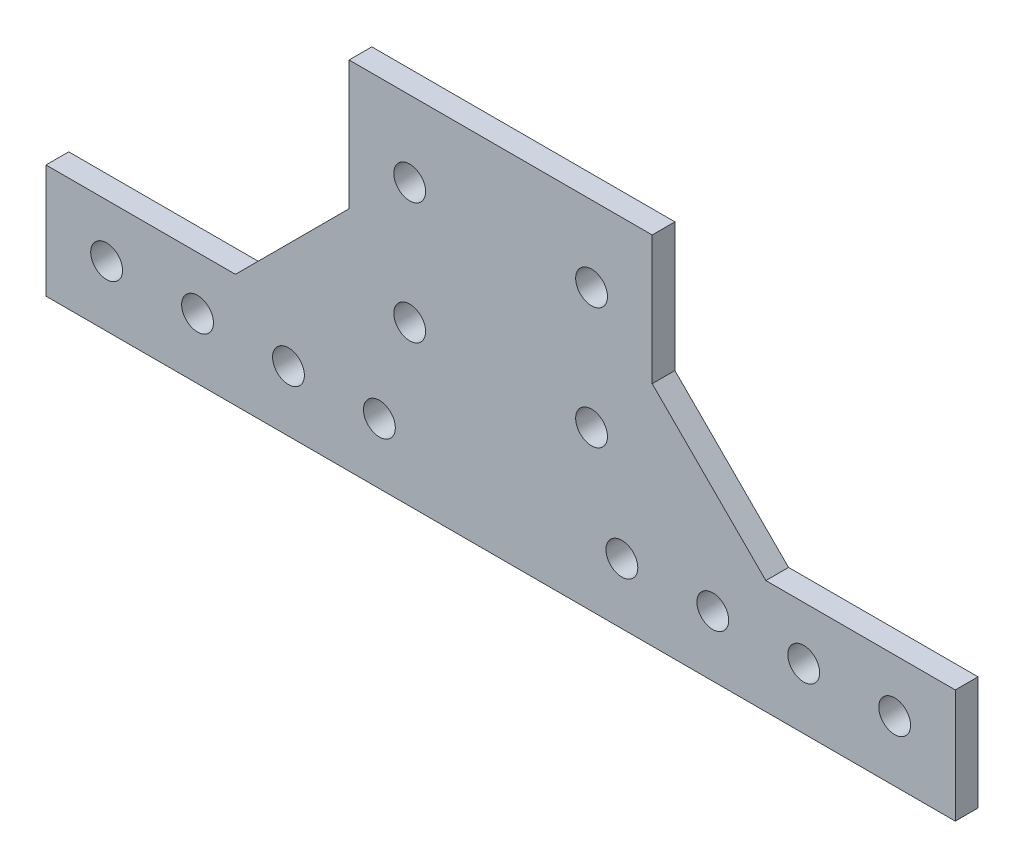
SolidWorks part; units mm, degrees
material "Thornel VCB-20 碳布"
ref_plane "前视基准面" through (0, 0, 0) normal (0, 0, 1) x (1, 0, 0)
ref_plane "上视基准面" through (0, 0, 0) normal (0, 1, 0) x (1, 0, 0)
ref_plane "右视基准面" through (0, 0, 0) normal (1, 0, 0) x (0, 0, -1)
other "Configuration Table"
sketch "草图1" plane through (0, 0, 0) normal (0, 0, 1) x (1, 0, 0)
  line L0 (0, 0) -> (0, 15)
  line L1 (0, 15) -> (25, 15)
  line L2 (25, 15) -> (40, 30)
  line L3 (40, 30) -> (40, 47)
  line L4 (40, 47) -> (80, 47)
  line L5 (80, 47) -> (80, 30)
  line L6 (80, 30) -> (95, 15)
  line L7 (95, 15) -> (120, 15)
  line L8 (120, 15) -> (120, 0)
  line L9 (120, 0) -> (0, 0)
  line L10 (80, 30) -> (40, 30) construction
  dimension "D1" = 40
  dimension "D2" = 15
  dimension "D3" = 45
  dimension "D4" = 45
  dimension "D5" = 15
  dimension "D6" = 40
  dimension "D7" = 32
extrude "凸台-拉伸1" add sketch "草图1" along normal blind 3
sketch "草图2" plane through (0, 0, 3) normal (0, 0, 1) x (1, 0, 0)
  circle A1 centre (48, 37) radius 2.1
  circle A2 centre (48, 37) radius 2.1
  circle A3 centre (72, 37) radius 2.1
  circle A4 centre (72, 37) radius 2.1
  circle A5 centre (48, 21) radius 2.1
  circle A6 centre (48, 21) radius 2.1
  circle A7 centre (72, 21) radius 2.1
  circle A8 centre (72, 21) radius 2.1
  circle A9 centre (112, 8) radius 2.1
  circle A10 centre (112, 8) radius 2.1
  circle A11 centre (76, 8) radius 2.1
  circle A12 centre (76, 8) radius 2.1
  circle A13 centre (88, 8) radius 2.1
  circle A14 centre (88, 8) radius 2.1
  circle A15 centre (8, 8) radius 2.1
  circle A16 centre (8, 8) radius 2.1
  circle A17 centre (20, 8) radius 2.1
  circle A18 centre (20, 8) radius 2.1
  circle A19 centre (100, 8) radius 2.1
  circle A20 centre (100, 8) radius 2.1
  circle A21 centre (32, 8) radius 2.1
  circle A22 centre (32, 8) radius 2.1
  circle A23 centre (44, 8) radius 2.1
  circle A24 centre (44, 8) radius 2.1
  circle A25 centre (432, 8) radius 2.1
  circle A26 centre (432, 8) radius 2.1
  circle A27 centre (444, 8) radius 2.1
  circle A28 centre (444, 8) radius 2.1
  circle A29 centre (524, 8) radius 2.1
  circle A30 centre (524, 8) radius 2.1
  circle A31 centre (536, 8) radius 2.1
  circle A32 centre (536, 8) radius 2.1
  circle A33 centre (456, 8) radius 2.1
  circle A34 centre (456, 8) radius 2.1
  circle A35 centre (468, 8) radius 2.1
  circle A36 centre (468, 8) radius 2.1
  circle A37 centre (500, 8) radius 2.1
  circle A38 centre (500, 8) radius 2.1
  circle A39 centre (512, 8) radius 2.1
  circle A40 centre (512, 8) radius 2.1
  dimension "D1" = 0
  dimension "D2" = 0
  dimension "D3" = 0
  dimension "D4" = 0
  dimension "D5" = 0
  dimension "D6" = 0
  dimension "D7" = 0
  dimension "D8" = 0
  dimension "D9" = 0
  dimension "D10" = 0
  dimension "D11" = 0
  dimension "D12" = 0
  dimension "D13" = 0
  dimension "D14" = 0
  dimension "D15" = 0
  dimension "D16" = 0
  dimension "D17" = 0
  dimension "D18" = 0
  dimension "D19" = 0
  dimension "D20" = 0
extrude "切除-拉伸1" cut sketch "草图2" against normal through all
